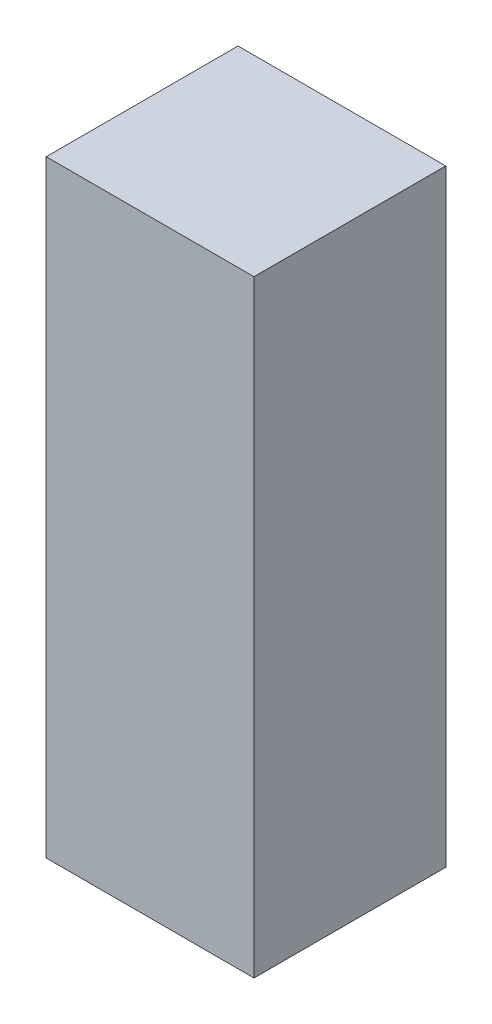
SolidWorks part; units mm, degrees
ref_plane "Front Plane" through (0, 0, 0) normal (0, 0, 1) x (1, 0, 0)
ref_plane "Top Plane" through (0, 0, 0) normal (0, 1, 0) x (1, 0, 0)
ref_plane "Right Plane" through (0, 0, 0) normal (1, 0, 0) x (0, 0, -1)
sketch "Sketch1" plane through (0, 0, 0) normal (0, 1, 0) x (1, 0, 0)
  line L1 (0, 0) -> (650, 0)
  line L2 (0, 0) -> (0, -600)
  line L3 (0, -600) -> (650, -600)
  line L4 (650, 0) -> (650, -600)
  dimension "D1" = 650
  dimension "D2" = 600
extrude "Boss-Extrude1" add sketch "Sketch1" along normal blind 1900
